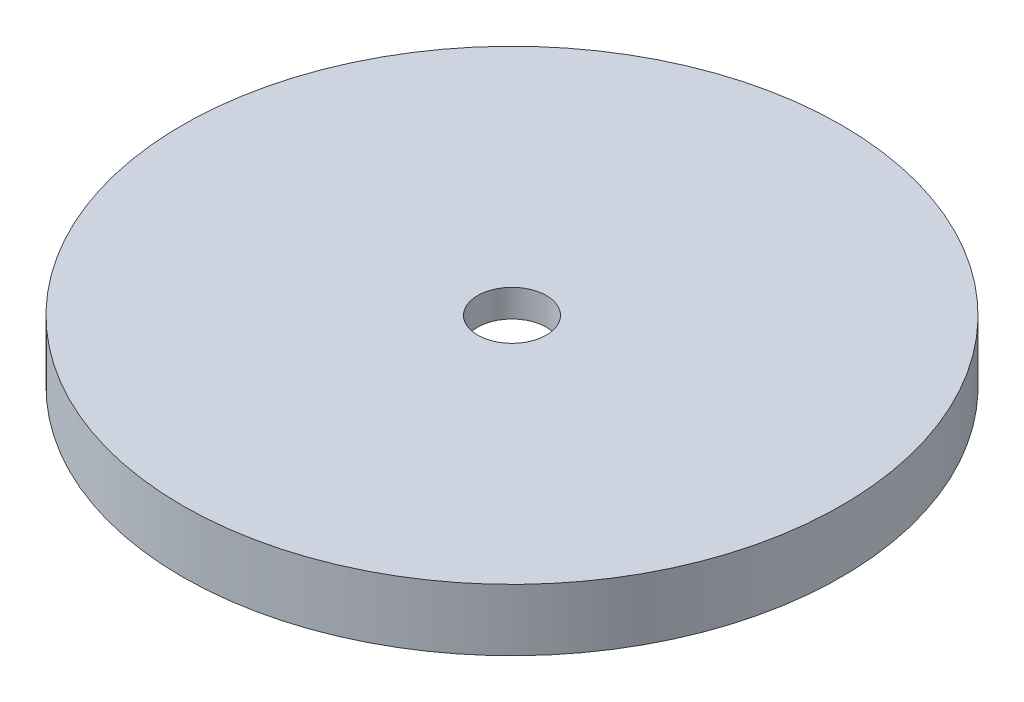
SolidWorks part; units mm, degrees
ref_plane "Front Plane" through (0, 0, 0) normal (0, 0, 1) x (1, 0, 0)
ref_plane "Top Plane" through (0, 0, 0) normal (0, 1, 0) x (1, 0, 0)
ref_plane "Right Plane" through (0, 0, 0) normal (1, 0, 0) x (0, 0, -1)
sketch "Sketch1" plane through (0, 0, 0) normal (0, 1, 0) x (1, 0, 0)
  circle A0 centre (0, 0) radius 19
  circle A1 centre (0, 0) radius 24
  dimension "D1" = 38
  dimension "D2" = 5
extrude "Boss-Extrude1" add sketch "Sketch1" along normal blind 2.5
sketch "Sketch2" plane through (0, 2.5, 0) normal (0, 1, 0) x (1, 0, 0)
  circle A1 centre (0, 0) radius 24
  circle A2 centre (0, 0) radius 24
  dimension "D1" = 0
extrude "Boss-Extrude2" add sketch "Sketch2" along normal blind 2
sketch "Sketch3" plane through (0, 0, 0) normal (0, -1, 0) x (1, 0, 0)
  circle A1 centre (0, 0) radius 21.25 construction
  circle A3 centre (0, 0) radius 2.5
  dimension "D1" = 5
  dimension "D2" = 42.5
extrude "Cut-Extrude1" cut sketch "Sketch3" against normal through all
